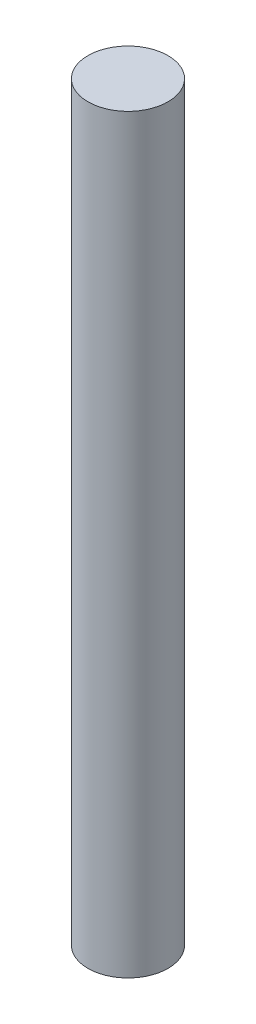
SolidWorks part; units mm, degrees
ref_plane "Front Plane" through (0, 0, 0) normal (0, 0, 1) x (1, 0, 0)
ref_plane "Top Plane" through (0, 0, 0) normal (0, 1, 0) x (1, 0, 0)
ref_plane "Right Plane" through (0, 0, 0) normal (1, 0, 0) x (0, 0, -1)
sketch "Sketch1" plane through (0, 0, 0) normal (0, 1, 0) x (1, 0, 0)
  circle A0 centre (0, 0) radius 8
  dimension "D1" = 16
extrude "Boss-Extrude1" add sketch "Sketch1" along normal mid plane 150
cosmetic thread "Cosmetic Thread1" parameters "D2"=13.797
